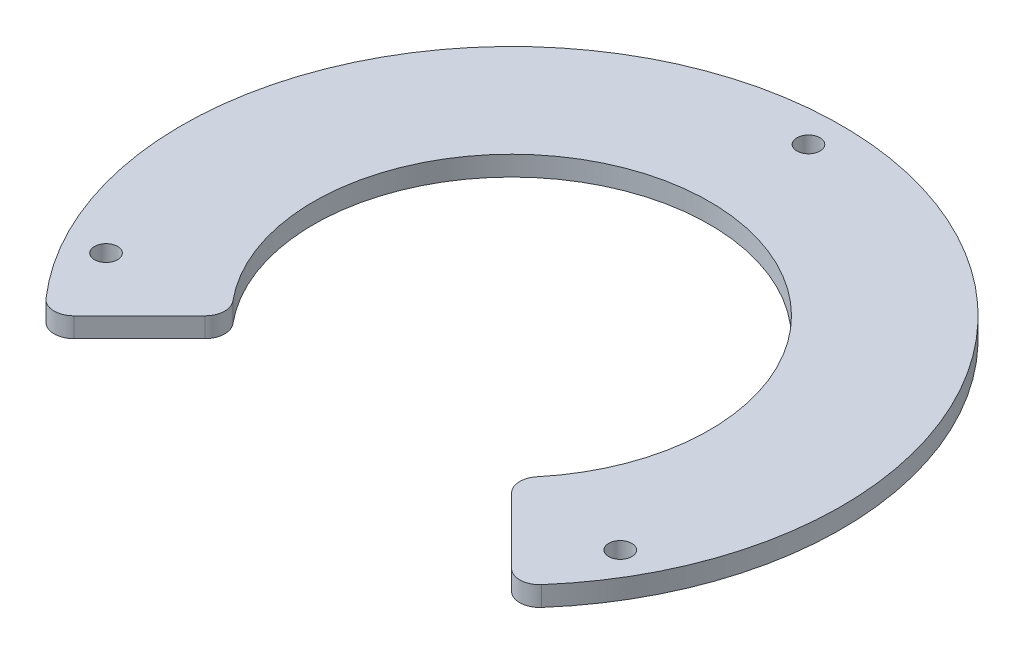
SolidWorks part; units mm, degrees
ref_plane "Front Plane" through (0, 0, 0) normal (0, 0, 1) x (1, 0, 0)
ref_plane "Top Plane" through (0, 0, 0) normal (0, 1, 0) x (1, 0, 0)
ref_plane "Right Plane" through (0, 0, 0) normal (1, 0, 0) x (0, 0, -1)
sketch "Sketch1" plane through (0, 0, 0) normal (0, 1, 0) x (1, 0, 0)
  circle A0 centre (0, 0) radius 30
  circle A1 centre (0, 0) radius 50
  circle A2 centre (0, 0) radius 45 construction
  circle A3 centre (0, 45) radius 1.75
  circle A4 centre (38.9711, -22.5) radius 1.75
  circle A5 centre (-38.9711, -22.5) radius 1.75
  point P13 (0, 0)
  dimension "D1" = 60
  dimension "D2" = 100
  dimension "D3" = 90
  dimension "D4" = 3.5
  dimension "D5" = 3
extrude "Boss-Extrude1" add sketch "Sketch1" along normal blind 3
sketch "Sketch2" plane through (0, 3, 0) normal (0, 1, 0) x (1, 0, 0)
  line L0 (0, 0) -> (-50, -50)
  line L5 (-50, -50) -> (50, -50)
  line L6 (50, -50) -> (0, 0)
  circle A0 centre (0, 0) radius 30 construction
  circle A1 centre (0, 0) radius 50 construction
  point P0 (0, -30)
  dimension "D1" = 90
extrude "Cut-Extrude1" cut sketch "Sketch2" against normal blind 14
fillet "Fillet1" radius 3 4 edges at (-21.2132, 1.5, 21.2132) (-35.3553, 1.5, 35.3553) (35.3553, 1.5, 35.3553) (21.2132, 1.5, 21.2132)
